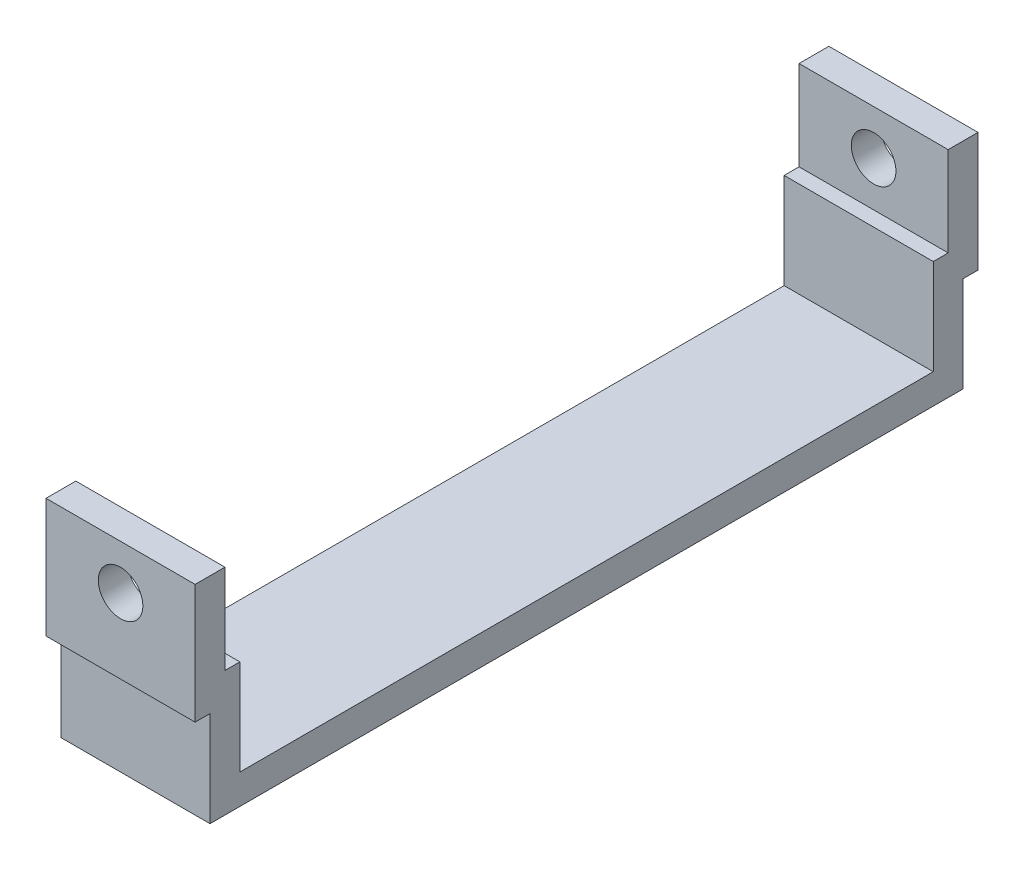
SolidWorks part; units mm, degrees
ref_plane "Front Plane" through (0, 0, 0) normal (0, 0, 1) x (1, 0, 0)
ref_plane "Top Plane" through (0, 0, 0) normal (0, 1, 0) x (1, 0, 0)
ref_plane "Right Plane" through (0, 0, 0) normal (1, 0, 0) x (0, 0, -1)
sketch "Sketch1" plane through (0, 0, 0) normal (1, 0, 0) x (0, 0, -1)
  line L0 (0, 0) -> (59.055, 0)
  line L1 (59.055, 0) -> (59.055, 8.128)
  line L2 (59.055, 8.128) -> (60.325, 8.128)
  line L3 (60.325, 8.128) -> (60.325, 15.748)
  line L4 (0, 0) -> (0, 8.128)
  line L5 (0, 8.128) -> (-1.27, 8.128)
  line L6 (-1.27, 8.128) -> (-1.27, 15.748)
  dimension "D1" = 59.055
  dimension "D2" = 8.128
  dimension "D3" = 7.62
  dimension "D4" = 1.27
  dimension "D5" = 1.27
  dimension "D6" = 8.128
extrude "Extrude-Thin1" add sketch "Sketch1" along normal blind 12.7 thin
hole_wizard "#6 Clearance Hole1" positions "Sketch3" profile "Sketch2" hole size "#6" standard "ANSI Inch"
sketch "Sketch3" plane through (0, 0, 1.27) normal (0, 0, -1) x (-1, 0, 0)
  line L0 (-12.7, 15.748) -> (0, 15.748) construction
  line L1 (0, 8.128) -> (0, 15.748) construction
  point P0 (-6.35, 11.938)
  dimension "D1" = 3.81
  dimension "D2" = 6.35
sketch "Sketch2" plane through (6.35, 11.938, 1.27) normal (1, 0, 0) x (0, 1, 0)
  line L0 (0, 0) -> (0, 8.7608)
  line L1 (0, 8.7608) -> (1.8986, 7.62)
  line L2 (1.8986, 7.62) -> (1.8986, 0)
  line L5 (1.8986, 0) -> (0, 0)
  line L10 (0, 8.7608) -> (-1.8986, 7.62) construction
  line L11 (0, -6.35) -> (0, 107.95) construction
  dimension "Hole Dia." = 3.7973
  dimension "Hole Depth" = 7.62
  dimension "Drill Angle" = 118
hole_wizard "#6 Clearance Hole2" positions "Sketch5" profile "Sketch4" hole size "#6" standard "ANSI Inch"
sketch "Sketch5" plane through (0, 0, -60.325) normal (0, 0, 1) x (1, 0, 0)
  line L0 (12.7, 15.748) -> (0, 15.748) construction
  line L1 (0, 15.748) -> (0, 8.128) construction
  point P0 (6.35, 11.938)
  dimension "D1" = 3.81
  dimension "D2" = 6.35
sketch "Sketch4" plane through (6.35, 11.938, -60.325) normal (1, 0, 0) x (0, -1, 0)
  line L0 (0, 0) -> (0, 8.7608)
  line L1 (0, 8.7608) -> (1.8986, 7.62)
  line L2 (1.8986, 7.62) -> (1.8986, 0)
  line L5 (1.8986, 0) -> (0, 0)
  line L10 (0, 8.7608) -> (-1.8986, 7.62) construction
  line L11 (0, -6.35) -> (0, 107.95) construction
  dimension "Hole Dia." = 3.7973
  dimension "Hole Depth" = 7.62
  dimension "Drill Angle" = 118
